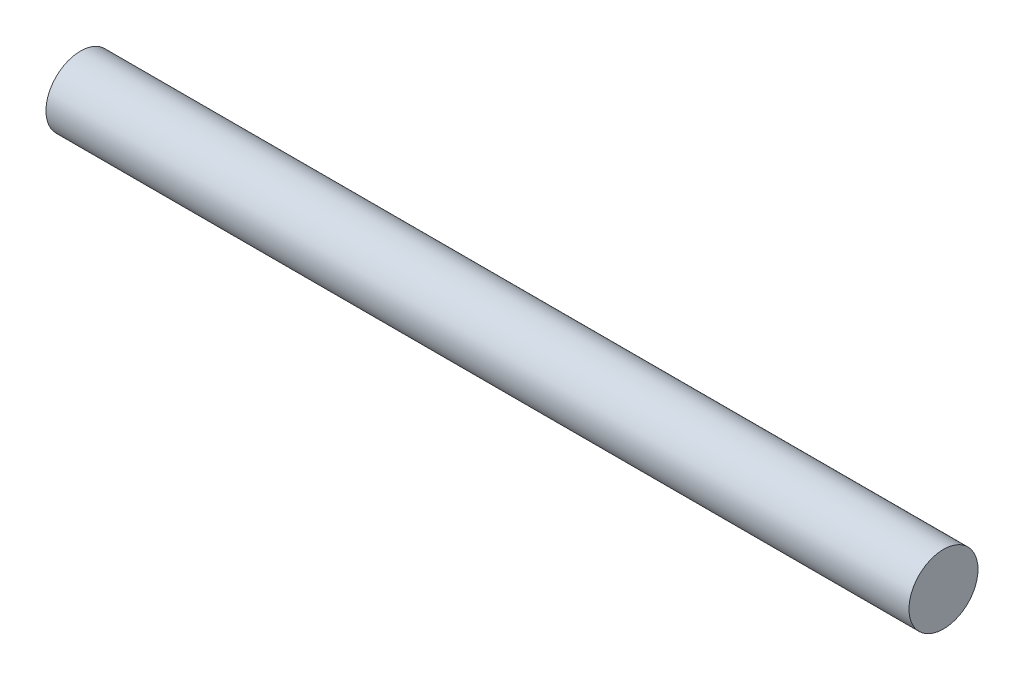
SolidWorks part; units mm, degrees
material "Ductile Iron"
ref_plane "Front Plane" through (0, 0, 0) normal (0, 0, 1) x (1, 0, 0)
ref_plane "Top Plane" through (0, 0, 0) normal (0, 1, 0) x (1, 0, 0)
ref_plane "Right Plane" through (0, 0, 0) normal (1, 0, 0) x (0, 0, -1)
sketch "Sketch1" plane through (0, 0, 0) normal (1, 0, 0) x (0, 0, -1)
  circle A4 centre (0, 0) radius 2.88
  dimension "D1" = 5.76
extrude "Boss-Extrude1" add sketch "Sketch1" along normal blind 72
